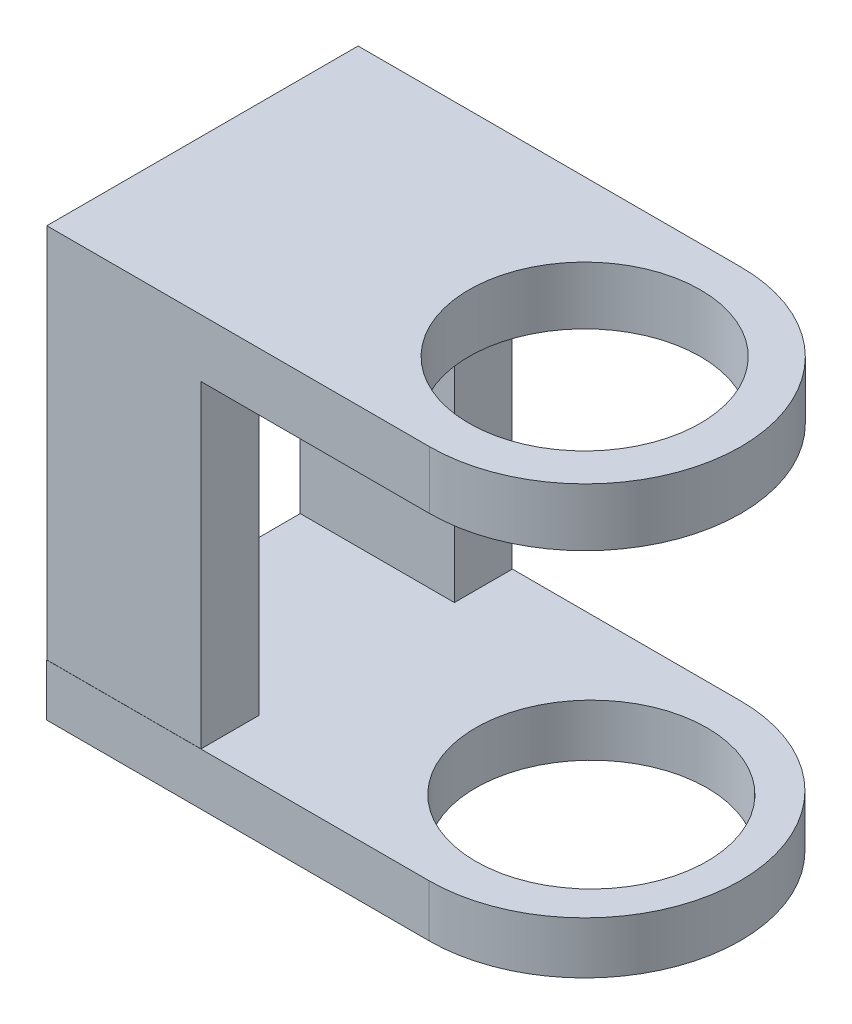
SolidWorks part; units mm, degrees
ref_plane "Alzado" through (0, 0, 0) normal (0, 0, 1) x (1, 0, 0)
ref_plane "Planta" through (0, 0, 0) normal (0, 1, 0) x (1, 0, 0)
ref_plane "Vista lateral" through (0, 0, 0) normal (1, 0, 0) x (0, 0, -1)
sketch "Croquis1" plane through (0, 0, 0) normal (0, 1, 0) x (1, 0, 0)
  line L0 (0, 0) -> (128.0795, 0) construction
  line L1 (0, 26.9043) -> (128.0795, 26.9043)
  line L2 (0, -26.9043) -> (128.0795, -26.9043)
  arc A0 (0, 26.9043) -> (0, -26.9043) centre (0, 0) ccw
  arc A1 (128.0795, -26.9043) -> (128.0795, 26.9043) centre (128.0795, 0) ccw
  point P3 (64.0398, 0)
extrude "Saliente-Extruir1" add sketch "Croquis1" along normal blind 10
sketch "Croquis2" plane through (0, 0, 0) normal (0, -1, 0) x (1, 0, 0)
  circle A0 centre (0, 0) radius 20
  dimension "D1" = 40
extrude "Cortar-Extruir1" cut sketch "Croquis2" against normal blind 10
sketch "Croquis3" plane through (0, 10, 0) normal (0, 1, 0) x (1, 0, 0)
  circle A0 centre (127.9803, 0) radius 20
  dimension "D1" = 40
extrude "Cortar-Extruir2" cut sketch "Croquis3" against normal blind 10
sketch "Croquis5" plane through (0, 0, 0) normal (0, -1, 0) x (-1, 0, 0)
  line L0 (0, -26.9043) -> (-128.0795, -26.9043) construction
  line L1 (-28.5585, -26.9043) -> (-88.5585, -26.9043)
  line L2 (-28.5585, -26.9043) -> (-28.5585, -16.9043)
  line L3 (-28.5585, -16.9043) -> (-88.5585, -16.9043)
  line L4 (-88.5585, -26.9043) -> (-88.5585, -16.9043)
  line L5 (-128.0795, 26.9043) -> (0, 26.9043) construction
  line L6 (-28.5585, 26.9043) -> (-88.5585, 26.9043)
  line L7 (-28.5585, 26.9043) -> (-28.5585, 16.9043)
  line L8 (-28.5585, 16.9043) -> (-88.5585, 16.9043)
  line L9 (-88.5585, 26.9043) -> (-88.5585, 16.9043)
  dimension "D1" = 10
  dimension "D2" = 10
  dimension "D3" = 60
  dimension "D4" = 60
extrude "Saliente-Extruir3" add sketch "Croquis5" along normal blind 55
sketch "Croquis7" plane through (0, -55, 0) normal (0, -1, 0) x (-1, 0, 0)
  line L0 (0, 0) -> (-127.9803, 0) construction
  line L1 (0, -26.9298) -> (-127.9803, -26.9298)
  line L2 (0, 26.9298) -> (-127.9803, 26.9298)
  arc A0 (0, -26.9298) -> (0, 26.9298) centre (0, 0) ccw
  arc A1 (-127.9803, 26.9298) -> (-127.9803, -26.9298) centre (-127.9803, 0) ccw
  point P4 (-63.9902, 0)
extrude "Saliente-Extruir4" add sketch "Croquis7" along normal blind 9
sketch "Croquis8" plane through (0, -64, 0) normal (0, -1, 0) x (-1, 0, 0)
  circle A0 centre (-129.14, 0) radius 20
  dimension "D1" = 40
extrude "Cortar-Extruir3" cut sketch "Croquis8" against normal blind 9
sketch "Croquis9" plane through (0, -64, 0) normal (0, -1, 0) x (-1, 0, 0)
  circle A0 centre (0, 0) radius 20
  dimension "D1" = 40
extrude "Cortar-Extruir4" cut sketch "Croquis9" against normal blind 10
ref_plane "Plano1" through (0, -64, 26.9298) normal (-1, 0, 0) x (0, 0, 1)
sketch "Croquis11" plane through (0, 0, 26.9298) normal (0, 0, 1) x (1, 0, 0)
  line L1 (61.9096, 29.4863) -> (-32.5433, 29.4863)
  line L2 (61.9096, 29.4863) -> (61.9096, -74.5672)
  line L3 (61.9096, -74.5672) -> (-32.5433, -74.5672)
  line L4 (-32.5433, 29.4863) -> (-32.5433, -74.5672)
sketch "Croquis14" plane through (0, -64, 0) normal (0, -1, 0) x (-1, 0, 0)
extrude "Cortar-Extruir6" cut sketch "Croquis11" against normal blind 54
ref_plane "Plano2" through (61.9096, 10, 26.705) normal (0, 1, 0) x (1, 0, 0)
sketch "Croquis15" plane through (61.9096, 10, 26.705) normal (0, 1, 0) x (1, 0, 0)
  line L1 (0, 0) -> (-76.607, 0)
  line L2 (0, 0) -> (0, -9.9108)
  line L3 (0, -9.9108) -> (-76.607, -9.9108)
  line L4 (-76.607, 0) -> (-76.607, -9.9108)
extrude "Cortar-Extruir7" cut sketch "Croquis15" against normal blind 76
